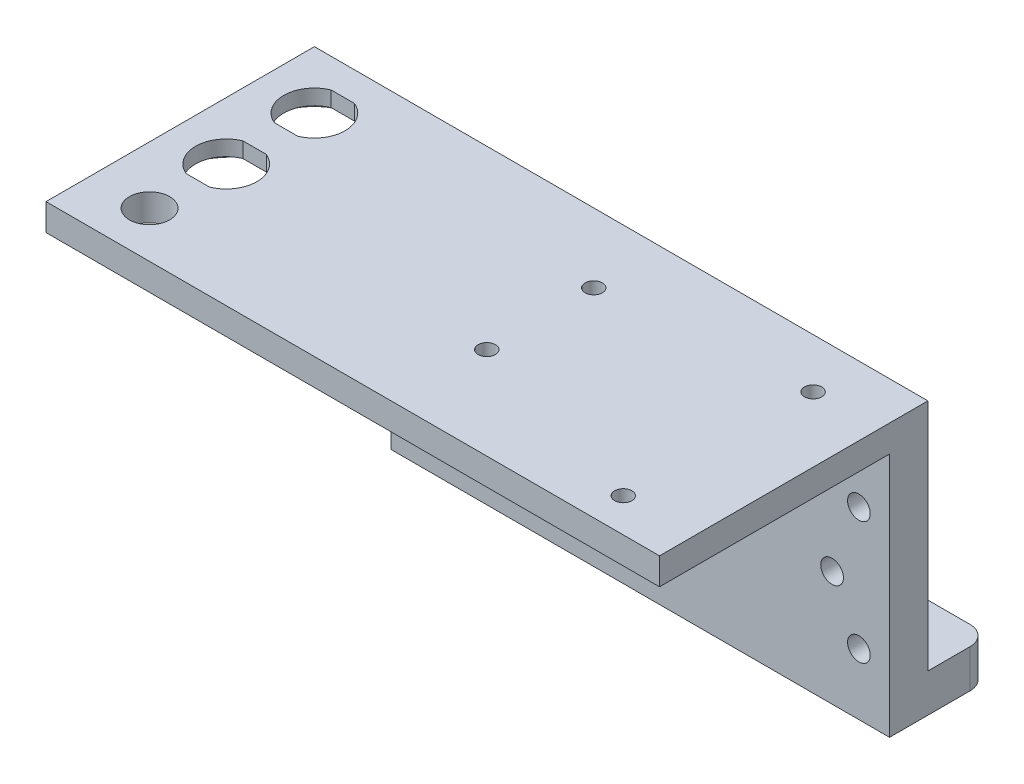
SolidWorks part; units mm, degrees
ref_plane "Front Plane" through (0, 0, 0) normal (0, 0, 1) x (1, 0, 0)
ref_plane "Top Plane" through (0, 0, 0) normal (0, 1, 0) x (1, 0, 0)
ref_plane "Right Plane" through (0, 0, 0) normal (1, 0, 0) x (0, 0, -1)
sketch "Sketch1" plane through (0, 0, 0) normal (0, 0, 1) x (1, 0, 0)
  line L1 (-65, -32) -> (65, -32)
  line L2 (-65, -32) -> (-65, 32)
  line L3 (-65, 32) -> (65, 32)
  line L4 (65, -32) -> (65, 32)
  line L5 (-65, -32) -> (65, 32) construction
  line L6 (-65, 32) -> (65, -32) construction
  line L7 (-57, 16) -> (57, 16) construction
  line L8 (-57, 16) -> (-57, -16) construction
  line L9 (-57, -16) -> (57, -16) construction
  line L10 (57, 16) -> (57, -16) construction
  line L11 (-57, 16) -> (57, -16) construction
  line L12 (-57, -16) -> (57, 16) construction
  circle A0 centre (57, 16) radius 2.9575
  circle A1 centre (57, -16) radius 2.9575
  circle A2 centre (-57, -16) radius 2.9575
  circle A3 centre (-57, 16) radius 2.9575
  point P0 (0, 0)
  point P6 (0, 0)
  dimension "D3" = 5.915
  dimension "D1" = 130
  dimension "D2" = 64
  dimension "D4" = 114
  dimension "D5" = 16
extrude "Boss-Extrude1" add sketch "Sketch1" along normal blind 10
sketch "Sketch2" plane through (0, -32, 0) normal (0, -1, 0) x (1, 0, 0)
  line L0 (65, 10) -> (65, 0) construction
  line L1 (-65, 0) -> (65, 0)
  line L2 (-65, 0) -> (-65, -16)
  line L3 (-65, -16) -> (65, -16)
  line L4 (65, 0) -> (65, -16)
  line L5 (0, -5.5) -> (0, 5.5) construction
  circle A0 centre (-40, -9) radius 2.75
  circle A2 centre (40, -9) radius 2.75
  dimension "D3" = 5.5
  dimension "D1" = 16
  dimension "D2" = 80
  dimension "D4" = 7
extrude "Boss-Extrude2" add sketch "Sketch2" against normal blind 10
sketch "Sketch3" plane through (0, 32, 0) normal (0, 1, 0) x (1, 0, 0)
  line L0 (65, -10) -> (65, 0) construction
  line L1 (-95, 0) -> (65, 0)
  line L2 (-95, 0) -> (-95, -70)
  line L3 (-95, -70) -> (65, -70)
  line L4 (65, 0) -> (65, -70)
  line L5 (65, 0) -> (-65, 0) construction
  line L6 (-6.6, -11.7) -> (62, -11.7) construction
  line L7 (-6.6, -11.7) -> (-6.6, -65) construction
  line L8 (-6.6, -65) -> (62, -65) construction
  line L9 (62, -11.7) -> (62, -65) construction
  line L10 (-83.0397, -30.6) -> (-76.9603, -30.6)
  line L11 (-83.0397, -45.4) -> (-76.9603, -45.4)
  line L12 (-83.0397, -7.6) -> (-76.9603, -7.6)
  line L13 (-83.0397, -22.4) -> (-76.9603, -22.4)
  line L14 (-65, 0) -> (-65, 16) construction
  circle A0 centre (48, -12.95) radius 2.25
  circle A1 centre (-4.1, -18.05) radius 2.25
  circle A2 centre (-4.1, -45.95) radius 2.25
  circle A3 centre (46.7, -61.15) radius 2.25
  arc A4 (-83.0397, -30.6) -> (-83.0397, -45.4) centre (-80, -38) ccw
  arc A5 (-76.9603, -45.4) -> (-76.9603, -30.6) centre (-80, -38) ccw
  arc A6 (-83.0397, -7.6) -> (-83.0397, -22.4) centre (-80, -15) ccw
  arc A7 (-76.9603, -22.4) -> (-76.9603, -7.6) centre (-80, -15) ccw
  circle A8 centre (-80, -58) radius 5.25
  circle A9 centre (-80, -38) radius 11 construction
  circle A10 centre (-80, -15) radius 11 construction
  dimension "D3" = 4.5
  dimension "D15" = 16
  dimension "D16" = 8
  dimension "D20" = 10.5
  dimension "D24" = 22
  dimension "D1" = 14
  dimension "D2" = 2.5
  dimension "D4" = 68.6
  dimension "D5" = 5.1
  dimension "D6" = 27.9
  dimension "D7" = 50.8
  dimension "D8" = 15.3
  dimension "D9" = 53.3
  dimension "D10" = 15.2
  dimension "D11" = 3
  dimension "D12" = 5
  dimension "D13" = 70
  dimension "D14" = 14.8
  dimension "D17" = 14.8
  dimension "D18" = 15
  dimension "D19" = 30
  dimension "D21" = 12
  dimension "D22" = 20
  dimension "D23" = 23
extrude "Boss-Extrude3" add sketch "Sketch3" along normal blind 7
sketch "Sketch4" plane through (0, 32, 0) normal (0, -1, 0) x (1, 0, 0)
  circle A0 centre (-80, 38) radius 12
  circle A1 centre (-80, 15) radius 12
  arc M8 (-83.0397, 30.6) -> (-83.0397, 45.4) centre (-80, 38) cw
  line M9 (-83.0397, 45.4) -> (-76.9603, 45.4)
  arc M10 (-76.9603, 45.4) -> (-76.9603, 30.6) centre (-80, 38) cw
  line M11 (-76.9603, 30.6) -> (-83.0397, 30.6)
  arc M16 (-83.0397, 7.6) -> (-83.0397, 22.4) centre (-80, 15) cw
  line M17 (-83.0397, 22.4) -> (-76.9603, 22.4)
  arc M18 (-76.9603, 22.4) -> (-76.9603, 7.6) centre (-80, 15) cw
  line M19 (-76.9603, 7.6) -> (-83.0397, 7.6)
  dimension "D1" = 24
extrude "Cut-Extrude1" cut sketch "Sketch4" against normal offset from surface (3 mm away) 4 contours A0 A1 M19 M16 M17 M18 | A1 A0 M11 M8 M9 M10 | A0 A1 up to face at (-80, 39, 15)
fillet "Fillet1" radius 5 2 edges at (-83.4278, 33.5, 26.5) (-76.5722, 33.5, 26.5)
sketch "Sketch5" plane through (0, 0, 0) normal (0, 0, -1) x (-1, 0, 0)
  line L0 (0, 39.05) -> (0, -39.05) construction
  line L1 (-65, -22) -> (65, -22) construction
  circle A0 centre (-50, -2) radius 2.9575
  circle A1 centre (50, -2) radius 2.9575
  circle A2 centre (-57, 16) radius 2.9575 construction
  dimension "D2" = 100
  dimension "D3" = 20
extrude "Cut-Extrude2" cut sketch "Sketch5" against normal up to next
fillet "Fillet2" radius 5 1 edges at (-65, -27, -16)
fillet "Fillet3" radius 5 1 edges at (65, -27, -16)
